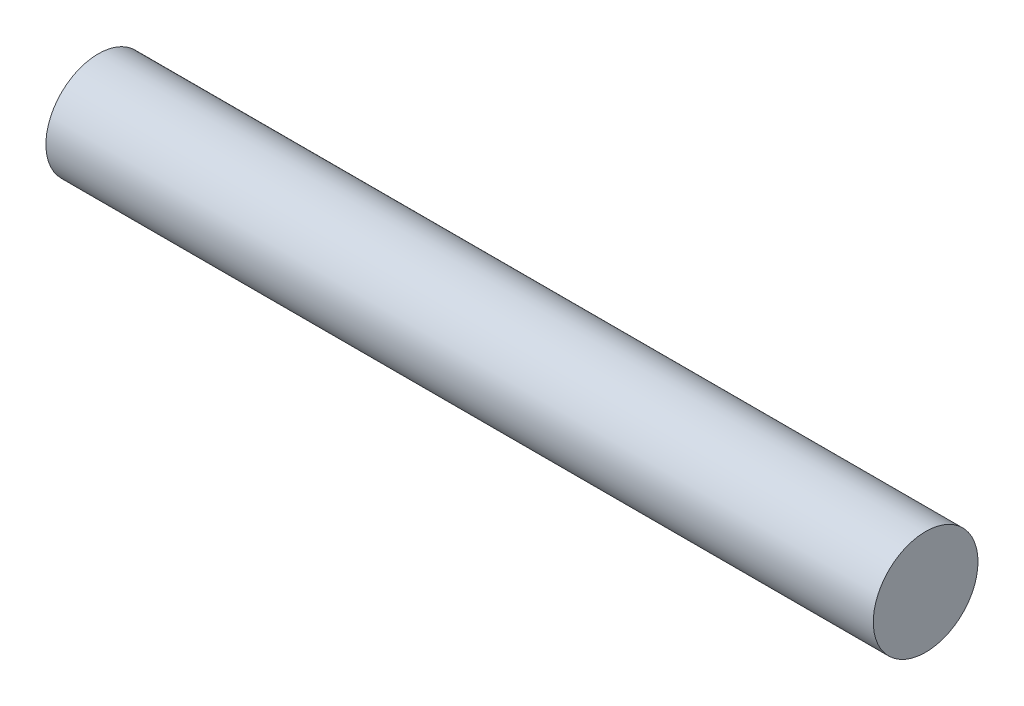
SolidWorks part; units mm, degrees
ref_plane "Plan de face" through (0, 0, 0) normal (0, 0, 1) x (1, 0, 0)
ref_plane "Plan de dessus" through (0, 0, 0) normal (0, 1, 0) x (1, 0, 0)
ref_plane "Plan de droite" through (0, 0, 0) normal (1, 0, 0) x (0, 0, -1)
sketch "Esquisse1" plane through (0, 0, 0) normal (1, 0, 0) x (0, 0, -1)
  circle A0 centre (0, 0) radius 10.125
  dimension "D1" = 20.25
extrude "Boss.-Extru.1" add sketch "Esquisse1" along normal blind 160
